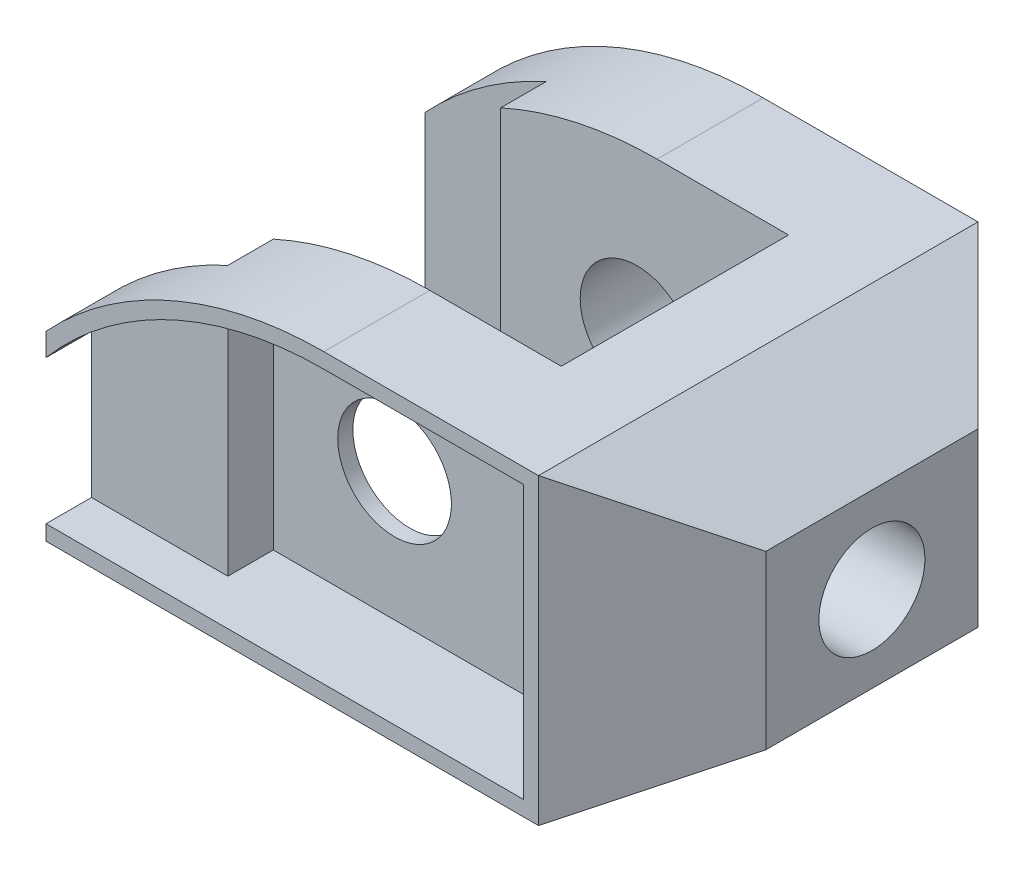
SolidWorks part; units mm, degrees
material "1060 Alloy"
ref_plane "Front Plane" through (0, 0, 0) normal (0, 0, 1) x (1, 0, 0)
ref_plane "Top Plane" through (0, 0, 0) normal (0, 1, 0) x (1, 0, 0)
ref_plane "Right Plane" through (0, 0, 0) normal (1, 0, 0) x (0, 0, -1)
sketch "Sketch1" plane through (0, 0, 0) normal (0, 0, 1) x (1, 0, 0)
  line L0 (0, 0) -> (0, 24)
  line L1 (0, 0) -> (65, 0)
  line L2 (65, 0) -> (80, 8.6603)
  line L3 (80, 8.6603) -> (80, 31.3397)
  line L4 (80, 31.3397) -> (65, 40)
  line L5 (65, 40) -> (36.6606, 40)
  arc A1 (0, 24) -> (36.6606, 40) centre (36.6606, -10) cw
  circle A2 centre (34, 19) radius 7.5
  dimension "D3" = 50
  dimension "D9" = 15
  dimension "D10" = 19
  dimension "D11" = 31
  dimension "D1" = 24
  dimension "D2" = 65
  dimension "D4" = 15
  dimension "D5" = 40
  dimension "D6" = 15
  dimension "D7" = 30
  dimension "D8" = 30
extrude "Boss-Extrude1" add sketch "Sketch1" along normal mid plane 58
sketch "Sketch2" plane through (0, 40, 0) normal (0, 1, 0) x (1, 0, 0)
  line L0 (0, -29) -> (0, 29) construction
  line L1 (0, 21) -> (16, 21)
  line L2 (0, 21) -> (0, -21)
  line L3 (0, -21) -> (16, -21)
  line L4 (16, 21) -> (16, 15)
  line L5 (36.6606, -29) -> (36.6606, 29) construction
  line L6 (54, -15) -> (16, -15)
  line L7 (54, -15) -> (54, 15)
  line L8 (54, 15) -> (16, 15)
  line L10 (16, -15) -> (16, -21)
  line L11 (36.6606, 29) -> (0, 29) construction
  line L12 (0, -29) -> (36.6606, -29) construction
  point P6 (36.6606, 0)
  dimension "D1" = 8
  dimension "D2" = 8
  dimension "D3" = 16
  dimension "D4" = 6
  dimension "D5" = 6
  dimension "D6" = 11
extrude "Cut-Extrude1" cut sketch "Sketch2" against normal blind 58
sketch "Sketch4" plane through (0, 0, 0) normal (0, 1, 0) x (1, 0, 0)
  line L0 (65, 29) -> (80, 29)
  line L1 (80, 29) -> (80, 14)
  line L2 (80, -29) -> (80, 29) construction
  line L3 (80, 14) -> (65, 29)
  line L4 (65, -29) -> (80, -29)
  line L5 (80, -29) -> (80, -14)
  line L6 (80, -14) -> (65, -29)
  line L7 (65, 29) -> (36.6606, 29) construction
  line L8 (65, -29) -> (36.6606, -29) construction
  dimension "D1" = 45
  dimension "D2" = 45
extrude "Cut-Extrude2" cut sketch "Sketch4" along normal blind 58
sketch "Sketch5" plane through (80, 0, 0) normal (1, 0, 0) x (0, 0, -1)
  line L0 (-29, 40) -> (-29, 0) construction
  line L1 (-29, 0) -> (29, 0) construction
  circle A0 centre (0, 20) radius 7
  dimension "D1" = 14
  dimension "D2" = 29
  dimension "D3" = 20
extrude "Cut-Extrude3" cut sketch "Sketch5" against normal blind 58
sketch "Sketch7" plane through (0, 0, 29) normal (0, 0, 1) x (1, 0, 0)
  line L0 (16, 0) -> (16, 35.5317) construction
  line L1 (16, 0) -> (16, 35.5317) construction
  line L2 (0, 2) -> (63, 2)
  line L3 (63, 2) -> (63, 38)
  line L4 (65, 0) -> (65, 40)
  line L5 (65, 40) -> (36.6606, 40)
  line L6 (0, 24) -> (0, 0)
  line L7 (0, 0) -> (65, 0)
  line L8 (65, 0) -> (65, 40)
  line L9 (65, 40) -> (36.6606, 40)
  line L11 (0, 0) -> (65, 0)
  line L12 (63, 38) -> (36.6606, 38)
  line L14 (0, 20.9839) -> (0, 2)
  arc A0 (36.6606, 38) -> (0, 20.9839) centre (36.6606, -10) ccw
  arc A1 (36.6606, 40) -> (0, 24) centre (36.6606, -10) ccw
  arc A2 (36.6606, 40) -> (0, 24) centre (36.6606, -10) ccw
  arc A3 (36.6606, 38) -> (1.4664, 22.64) centre (36.6606, -10) ccw construction
  dimension "D1" = 0
  dimension "D2" = 2
extrude "Cut-Extrude6" cut sketch "Sketch7" against normal blind 6 contours L3 L12 A0 L14 L2
sketch "Sketch8" plane through (0, 0, 23) normal (0, 0, 1) x (1, 0, 0)
  line L2 (18, 2) -> (18, 34.2242)
  line L4 (0, 2) -> (63, 2)
  line L5 (63, 2) -> (63, 38)
  line L6 (63, 38) -> (36.6606, 38)
  line L7 (0, 20.9839) -> (0, 2)
  line L8 (18, 2) -> (63, 2)
  line L9 (63, 2) -> (63, 38)
  line L10 (63, 38) -> (36.6606, 38)
  arc A1 (36.6606, 38) -> (0, 20.9839) centre (36.6606, -10) ccw
  arc A2 (36.6606, 38) -> (18, 34.2242) centre (36.6606, -10) ccw
  point P4 (0, 0)
  point P6 (17.5972, 2)
  point P7 (17.548, 34.2242)
  point P9 (18.0025, 2)
  dimension "D2" = 2
  dimension "D1" = 0
extrude "Cut-Extrude8" cut sketch "Sketch8" against normal blind 6
equation "\"a\"= 58mm"
equation "\"b\"= 40mm"
equation "\"c\"= 65mm"
